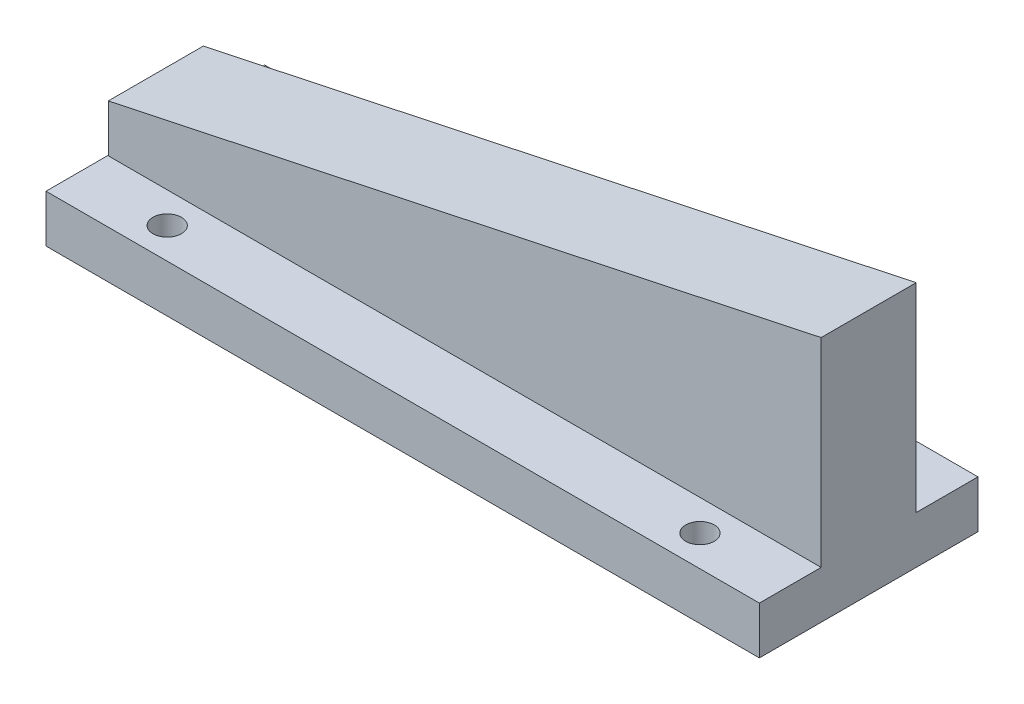
SolidWorks part; units mm, degrees
ref_plane "Front Plane" through (0, 0, 0) normal (0, 0, 1) x (1, 0, 0)
ref_plane "Top Plane" through (0, 0, 0) normal (0, 1, 0) x (1, 0, 0)
ref_plane "Right Plane" through (0, 0, 0) normal (1, 0, 0) x (0, 0, -1)
sketch "Sketch1" plane through (0, 0, 0) normal (0, 1, 0) x (1, 0, 0)
  line L1 (-75, -10) -> (75, -10)
  line L2 (-75, -10) -> (-75, 10)
  line L3 (-75, 10) -> (75, 10)
  line L4 (75, -10) -> (75, 10)
  line L5 (-75, -10) -> (75, 10) construction
  line L6 (-75, 10) -> (75, -10) construction
  point P0 (0, 0)
  dimension "D1" = 20
  dimension "D2" = 150
extrude "Boss-Extrude1" add sketch "Sketch1" along normal mid plane 20
sketch "Sketch2" plane through (0, 0, 0) normal (0, 0, 1) x (1, 0, 0)
  line L0 (-75, 10) -> (75, 10)
  line L1 (75, 10) -> (75, -10) construction
  line L2 (-75, 10) -> (75, 10) construction
  line L3 (75, 10) -> (75, 41.8835)
  line L4 (75, 41.8835) -> (-75, 10)
  dimension "D1" = 12
extrude "Boss-Extrude2" add sketch "Sketch2" along normal mid plane 20
sketch "Sketch7" plane through (0, 0, 0) normal (0, 0, 1) x (1, 0, 0)
  line L0 (75, 0) -> (75, -10)
  line L1 (75, 0) -> (-75.0999, 0)
  line L2 (75, -10) -> (-75.0999, -10)
  line L3 (-75.0999, 0) -> (-75.0999, -10)
  line L4 (75, 41.8835) -> (75, -10) construction
  dimension "D1" = 10
extrude "Boss-Extrude3" add sketch "Sketch7" along normal mid plane 46
sketch "Sketch8" plane through (0, 0, 10) normal (0, 1, 0) x (1, 0, 0)
  line L6 (-56.0999, 26.5) -> (56, 26.5) construction
  line L7 (56, 26.5) -> (56, -6.5) construction
  line L8 (56, -6.5) -> (-56.0999, -6.5) construction
  line L9 (-56.0999, -6.5) -> (-56.0999, 26.5) construction
  line L10 (75, -13) -> (75, 0) construction
  line L11 (-75.0999, -13) -> (-75.0999, 33) construction
  line L12 (75, 33) -> (-75.0999, 33) construction
  line L13 (75, -13) -> (-75.0999, -13) construction
  circle A0 centre (-56.0999, 26.5) radius 3
  circle A1 centre (56, 26.5) radius 3
  circle A2 centre (56, -6.5) radius 3
  circle A3 centre (-56.0999, -6.5) radius 3
  dimension "D1" = 6
  dimension "D2" = 19
  dimension "D3" = 19
  dimension "D4" = 6.5
  dimension "D5" = 6.5
extrude "Cut-Extrude4" cut sketch "Sketch8" against normal blind 46
